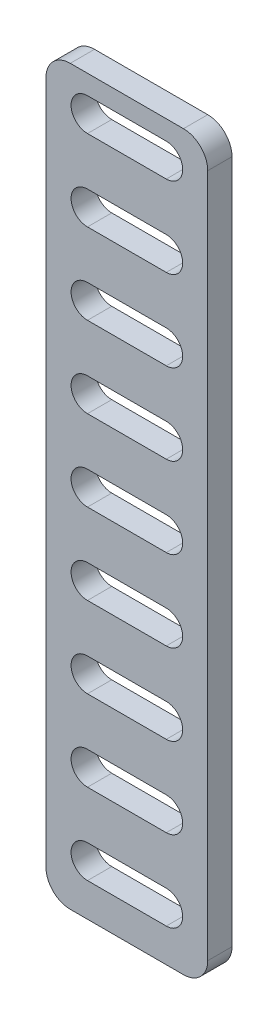
SolidWorks part; units mm, degrees
ref_plane "Front Plane" through (0, 0, 0) normal (0, 0, 1) x (1, 0, 0)
ref_plane "Top Plane" through (0, 0, 0) normal (0, 1, 0) x (1, 0, 0)
ref_plane "Right Plane" through (0, 0, 0) normal (1, 0, 0) x (0, 0, -1)
sketch "Sketch1" plane through (0, 0, 0) normal (0, 0, 1) x (1, 0, 0)
  line L6 (-81.0668, 33.9086) -> (-101.0668, 33.9086)
  line L7 (-81.0668, 124.5092) -> (-101.0668, 124.5092)
  line L8 (-91.0668, 24.5794) -> (-91.0668, 142.0861) construction
  line L9 (-86.196, 40.0812) -> (-95.9377, 40.0812) construction
  line L10 (-101.0668, 124.5092) -> (-101.0668, 33.9086)
  line L11 (-81.0668, 124.5092) -> (-81.0668, 33.9086)
  line L12 (-86.196, 38.0536) -> (-95.9377, 38.0536)
  line L13 (-86.196, 42.1089) -> (-95.9377, 42.1089)
  line L14 (-86.196, 50.0812) -> (-95.9377, 50.0812) construction
  line L15 (-86.196, 48.0536) -> (-95.9377, 48.0536)
  line L16 (-86.196, 52.1089) -> (-95.9377, 52.1089)
  line L17 (-86.196, 60.0812) -> (-95.9377, 60.0812) construction
  line L20 (-86.196, 58.0536) -> (-95.9377, 58.0536)
  line L23 (-86.196, 62.1089) -> (-95.9377, 62.1089)
  line L26 (-86.196, 70.0812) -> (-95.9377, 70.0812) construction
  line L29 (-86.196, 68.0536) -> (-95.9377, 68.0536)
  line L32 (-86.196, 72.1089) -> (-95.9377, 72.1089)
  line L35 (-86.196, 80.0812) -> (-95.9377, 80.0812) construction
  line L38 (-86.196, 78.0536) -> (-95.9377, 78.0536)
  line L39 (-86.196, 82.1089) -> (-95.9377, 82.1089)
  line L40 (-86.196, 90.0812) -> (-95.9377, 90.0812) construction
  line L41 (-86.196, 88.0536) -> (-95.9377, 88.0536)
  line L42 (-86.196, 92.1089) -> (-95.9377, 92.1089)
  line L43 (-86.196, 100.0812) -> (-95.9377, 100.0812) construction
  line L44 (-86.196, 98.0536) -> (-95.9377, 98.0536)
  line L45 (-86.196, 102.1089) -> (-95.9377, 102.1089)
  line L46 (-86.196, 110.0812) -> (-95.9377, 110.0812) construction
  line L47 (-86.196, 108.0536) -> (-95.9377, 108.0536)
  line L48 (-86.196, 112.1089) -> (-95.9377, 112.1089)
  line L49 (-86.196, 120.0812) -> (-95.9377, 120.0812) construction
  line L50 (-86.196, 118.0536) -> (-95.9377, 118.0536)
  line L51 (-86.196, 122.1089) -> (-95.9377, 122.1089)
  line L52 (-84.0668, 124.5092) -> (-81.0668, 124.5092) construction
  arc A0 (-86.196, 38.0536) -> (-86.196, 42.1089) centre (-86.196, 40.0812) ccw
  arc A1 (-95.9377, 42.1089) -> (-95.9377, 38.0536) centre (-95.9377, 40.0812) ccw
  arc A2 (-86.196, 48.0536) -> (-86.196, 52.1089) centre (-86.196, 50.0812) ccw
  arc A3 (-95.9377, 52.1089) -> (-95.9377, 48.0536) centre (-95.9377, 50.0812) ccw
  arc A18 (-86.196, 58.0536) -> (-86.196, 62.1089) centre (-86.196, 60.0812) ccw
  arc A19 (-95.9377, 62.1089) -> (-95.9377, 58.0536) centre (-95.9377, 60.0812) ccw
  arc A20 (-86.196, 68.0536) -> (-86.196, 72.1089) centre (-86.196, 70.0812) ccw
  arc A21 (-95.9377, 72.1089) -> (-95.9377, 68.0536) centre (-95.9377, 70.0812) ccw
  arc A22 (-86.196, 78.0536) -> (-86.196, 82.1089) centre (-86.196, 80.0812) ccw
  arc A23 (-95.9377, 82.1089) -> (-95.9377, 78.0536) centre (-95.9377, 80.0812) ccw
  arc A24 (-86.196, 88.0536) -> (-86.196, 92.1089) centre (-86.196, 90.0812) ccw
  arc A25 (-95.9377, 92.1089) -> (-95.9377, 88.0536) centre (-95.9377, 90.0812) ccw
  arc A26 (-86.196, 98.0536) -> (-86.196, 102.1089) centre (-86.196, 100.0812) ccw
  arc A27 (-95.9377, 102.1089) -> (-95.9377, 98.0536) centre (-95.9377, 100.0812) ccw
  arc A28 (-86.196, 108.0536) -> (-86.196, 112.1089) centre (-86.196, 110.0812) ccw
  arc A29 (-95.9377, 112.1089) -> (-95.9377, 108.0536) centre (-95.9377, 110.0812) ccw
  arc A30 (-86.196, 118.0536) -> (-86.196, 122.1089) centre (-86.196, 120.0812) ccw
  arc A31 (-95.9377, 122.1089) -> (-95.9377, 118.0536) centre (-95.9377, 120.0812) ccw
  point P8 (-91.0668, 40.0812)
  point P15 (-91.0668, 50.0812)
  point P23 (-91.0668, 60.0812)
  point P30 (-91.0668, 70.0812)
  point P37 (-91.0668, 80.0812)
  point P44 (-91.0668, 90.0812)
  point P51 (-91.0668, 100.0812)
  point P58 (-91.0668, 110.0812)
  point P65 (-91.0668, 120.0812)
  dimension "D1" = 10
  dimension "D3" = 20
  dimension "D4" = 10
  dimension "D2" = 8
extrude "Boss-Extrude1" add sketch "Sketch1" along normal blind 3
fillet "Fillet1" radius 3 4 edges at (-101.0668, 124.5092, 1.5) (-81.0668, 124.5092, 1.5) (-101.0668, 33.9086, 1.5) (-81.0668, 33.9086, 1.5)
